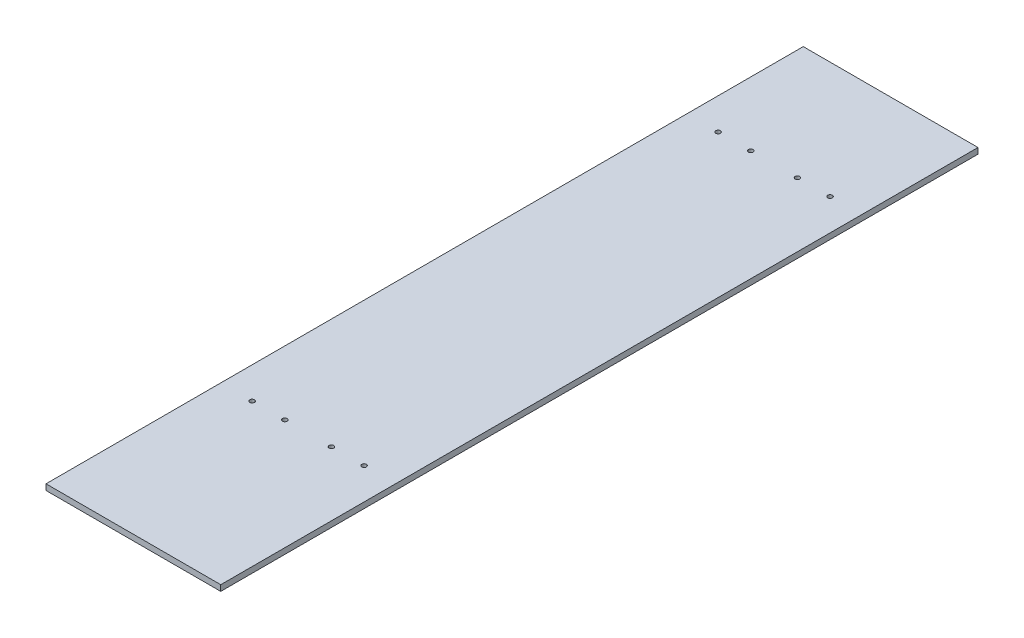
SolidWorks part; units mm, degrees
ref_plane "Front Plane" through (0, 0, 0) normal (0, 0, 1) x (1, 0, 0)
ref_plane "Top Plane" through (0, 0, 0) normal (0, 1, 0) x (1, 0, 0)
ref_plane "Right Plane" through (0, 0, 0) normal (1, 0, 0) x (0, 0, -1)
sketch "Sketch1" plane through (0, 0, 0) normal (0, 0, 1) x (1, 0, 0)
  line L1 (75, -2.5) -> (-75, -2.5)
  line L2 (75, -2.5) -> (75, 2.5)
  line L3 (75, 2.5) -> (-75, 2.5)
  line L4 (-75, -2.5) -> (-75, 2.5)
  line L5 (75, -2.5) -> (-75, 2.5) construction
  line L6 (75, 2.5) -> (-75, -2.5) construction
  point P0 (0, 0)
  dimension "D1" = 5
  dimension "D2" = 150
extrude "Boss-Extrude1" add sketch "Sketch1" along normal blind 650
sketch "Sketch2" plane through (0, 2.5, 0) normal (0, 1, 0) x (1, 0, 0)
  line L0 (-34, -500) -> (34, -500) construction
  line L1 (-75, -650) -> (-75, 0) construction
  line L2 (75, -650) -> (-75, -650) construction
  line L3 (0, -650) -> (0, -547.2076) construction
  line L5 (-48, -300) -> (34, -300) construction
  circle A0 centre (-20, -500) radius 2
  circle A1 centre (-48, -500) radius 2
  circle A2 centre (48, -500) radius 2
  circle A3 centre (20, -500) radius 2
  circle A4 centre (48, -100) radius 2
  circle A5 centre (20, -100) radius 2
  circle A6 centre (-20, -100) radius 2
  circle A7 centre (-48, -100) radius 2
  point P6 (0, -500)
  dimension "D2" = 4
  dimension "D3" = 4
  dimension "D1" = 68
  dimension "D4" = 14
  dimension "D5" = 14
  dimension "D6" = 75
  dimension "D7" = 150
  dimension "D8" = 200
extrude "Cut-Extrude1" cut sketch "Sketch2" against normal up to next
